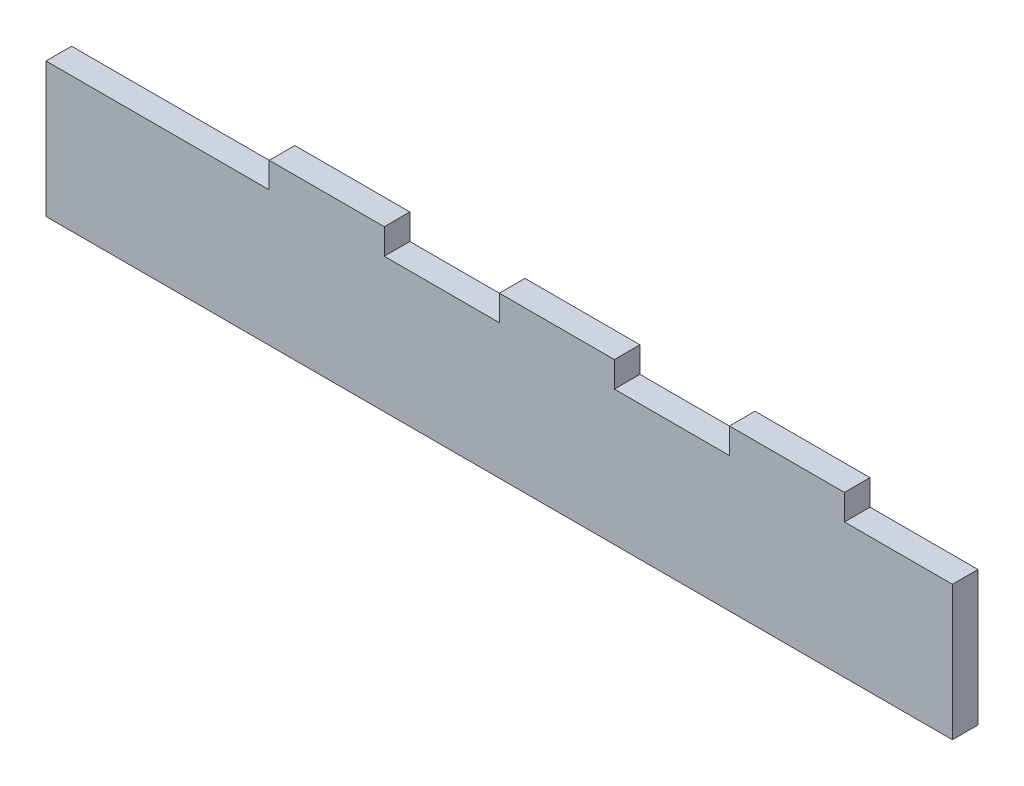
SolidWorks part; units mm, degrees
ref_plane "Front Plane" through (0, 0, 0) normal (0, 0, 1) x (1, 0, 0)
ref_plane "Top Plane" through (0, 0, 0) normal (0, 1, 0) x (1, 0, 0)
ref_plane "Right Plane" through (0, 0, 0) normal (1, 0, 0) x (0, 0, -1)
sketch "Sketch1" plane through (0, 0, 0) normal (0, 0, 1) x (1, 0, 0)
  line L1 (0, 0) -> (170.942, 0)
  line L2 (0, 0) -> (0, 30.226)
  line L3 (0, 30.226) -> (170.942, 30.226)
  line L4 (170.942, 0) -> (170.942, 30.226)
  dimension "D1" = 170.942
  dimension "D2" = 30.226
extrude "Boss-Extrude1" add sketch "Sketch1" along normal blind 4.826
sketch "Sketch2" plane through (0, 0, 0) normal (0, 0, -1) x (-1, 0, 0)
  line L0 (0, 25.4) -> (-42.0951, 25.4) construction
  line L1 (0, 25.4) -> (0, 30.226) construction
  line L2 (0, 30.226) -> (-42.0951, 30.226) construction
  line L3 (-42.0951, 30.226) -> (-42.0951, 25.4) construction
  line L4 (-63.7923, 25.4) -> (-85.4895, 25.4) construction
  line L5 (-85.4895, 30.226) -> (-85.4895, 25.4) construction
  line L6 (-63.7923, 30.226) -> (-63.7923, 25.4) construction
  line L7 (-63.7923, 30.226) -> (-85.4895, 30.226) construction
  line L8 (-107.1867, 25.4) -> (-128.8839, 25.4) construction
  line L9 (-128.8839, 30.226) -> (-128.8839, 25.4) construction
  line L10 (-107.1867, 30.226) -> (-107.1867, 25.4) construction
  line L11 (-107.1867, 30.226) -> (-128.8839, 30.226) construction
  line L12 (-150.5811, 25.4) -> (-170.979, 25.4) construction
  line L13 (-150.5811, 30.226) -> (-150.5811, 25.4) construction
  line L14 (-170.979, 25.4) -> (-170.979, 30.226) construction
  line L15 (-150.5811, 30.226) -> (-170.979, 30.226) construction
  line L16 (0, 25.4) -> (-42.0951, 25.4)
  line L17 (0, 25.4) -> (0, 30.226)
  line L18 (0, 30.226) -> (-42.0951, 30.226)
  line L19 (-42.0951, 30.226) -> (-42.0951, 25.4)
  line L20 (-63.7923, 25.4) -> (-85.4895, 25.4)
  line L21 (-85.4895, 30.226) -> (-85.4895, 25.4)
  line L22 (-63.7923, 30.226) -> (-63.7923, 25.4)
  line L23 (-63.7923, 30.226) -> (-85.4895, 30.226)
  line L24 (-107.1867, 25.4) -> (-128.8839, 25.4)
  line L25 (-128.8839, 30.226) -> (-128.8839, 25.4)
  line L26 (-107.1867, 30.226) -> (-107.1867, 25.4)
  line L27 (-107.1867, 30.226) -> (-128.8839, 30.226)
  line L28 (-150.5811, 25.4) -> (-170.979, 25.4)
  line L29 (-150.5811, 30.226) -> (-150.5811, 25.4)
  line L30 (-170.979, 25.4) -> (-170.979, 30.226)
  line L31 (-150.5811, 30.226) -> (-170.979, 30.226)
extrude "Cut-Extrude1" cut sketch "Sketch2" against normal through all
equation "\"MDF\"= 0.19in"
equation "\"PVCID\" = 2.067in"
equation "\"PVCOD\" = 2.375in"
equation "\"GenDiameter\"= 60mm"
equation "\"GenCutDiameter\" = 1.8in"
equation "\"GenCutDistance\" = 1"
equation "\"TowerHeight\" = 6in"
equation "\"TowerFrontBase\" = 3in"
equation "\"FunnelHeight\" = 1in"
equation "\"FunnelAngle\" = 20"
equation "\"TowerSideBase\" = 3in"
equation "\"TowerPanelLength\" = 2in"
equation "\"TowerPanelLeeway\" = 0.5in"
equation "\"BaseLength\" = 9in"
equation "\"BaseWidth\" = 10in"
equation "\"WheelHoleLength\" = 3.25in"
equation "\"WheelHoleWidth\" = 26mm"
equation "\"WheelHoleFromBack\" = 1.5in"
equation "\"DropLength\" = 1in"
equation "\"DropWidth\" = 8.5in"
equation "\"BumperWidth\" = 2in"
equation "\"SmallHexDiameter\" = 0.185in"
equation "\"SmallHexHeight\" = 0.701in"
equation "\"ScrewSize\" = 0.106in"
equation "\"BigHexDiameter\" = 0.251in"
equation "\"BigHexHeight\" = 0.374in"
equation "\"PCBThickness\" = 0.066in"
equation "\"ConnectorHeight\" = 0.517in"
equation "\"BoardHeight\" = 0.583in"
equation "\"UnoStackHeight\" = 1.351in"
equation "\"UnoStackWidth\" = 3.053in"
equation "\"UnoStackLength\" = 3.152in"
equation "\"HBridgeWidth\" = 1.797in"
equation "\"HBridgeLength\" = 2.236in"
equation "\"DSWidth\" = 1.820in"
equation "\"DSLength\" = 1.833in"
equation "\"StepperWidth\" = 1.799in"
equation "\"StepperLength\" = 2.248in"
equation "\"ULNWidth\" = 1.304in"
equation "\"ULNLength\" = 1.545in"
equation "\"VSwitchHeight\" = 0.392in"
equation "\"VSwitchWidth\" = 0.637in"
equation "\"VSwitchLength\" = 1.097in"
equation "\"SkateWheelDiameter\" = 80mm"
equation "\"SkateWheelThickness\" = 24mm"
equation "\"BaseDistance\" = 3in"
equation "\"DummyVar\" = 2in"
equation "\"D2@Sketch1\"=\"MDF\"+1in"
equation "\"D1@Boss-Extrude1\"=\"MDF\""
